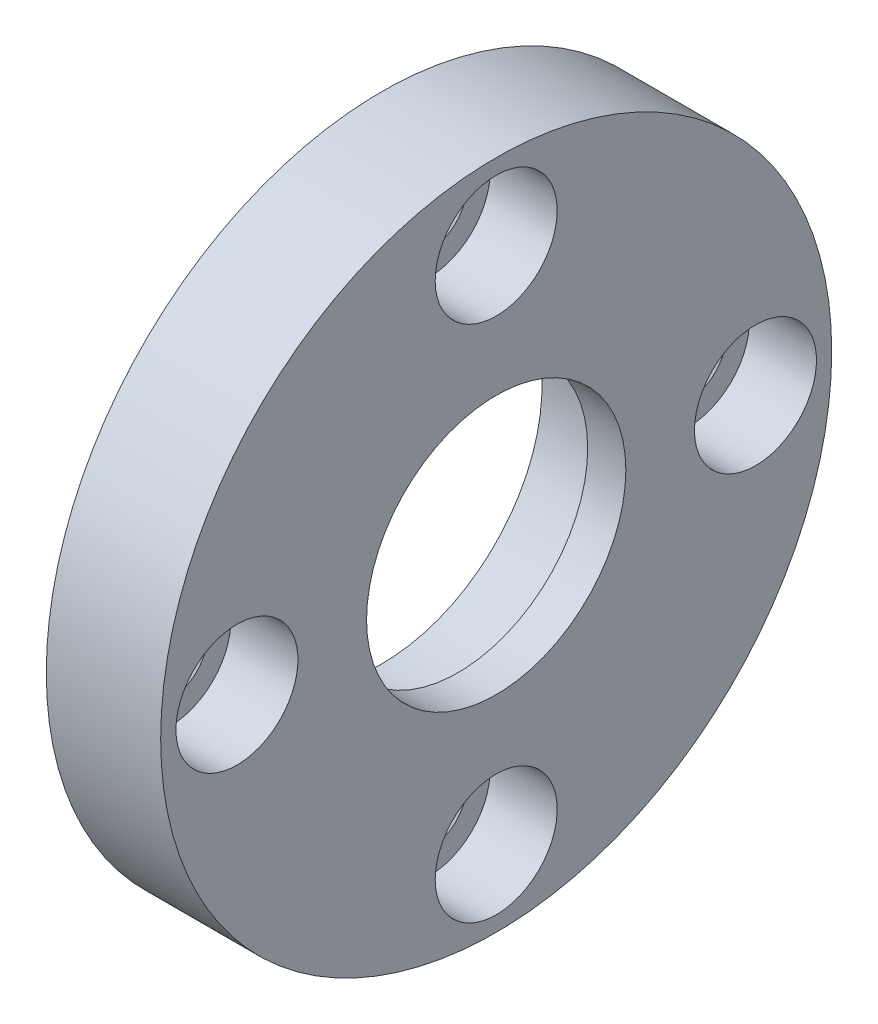
SolidWorks part; units mm, degrees
ref_plane "正面" through (0, 0, 0) normal (0, 0, 1) x (1, 0, 0)
ref_plane "平面" through (0, 0, 0) normal (0, 1, 0) x (1, 0, 0)
ref_plane "右側面" through (0, 0, 0) normal (1, 0, 0) x (0, 0, -1)
ref_plane "平面1" through (0, 0, 0) normal (0, 0, 1) x (1, 0, 0)
sketch "ｽｹｯﾁ1" plane through (0, 0, 0) normal (0, 0, 1) x (1, 0, 0)
  line L0 (-3.75, 0) -> (-3.75, 22)
  line L1 (-3.75, 22) -> (3.75, 22)
  line L2 (3.75, 22) -> (3.75, 0)
  line L3 (3.75, 0) -> (-3.75, 0)
  line L4 (3.75, 0) -> (-3.75, 0) construction
revolve "回転1" add sketch "ｽｹｯﾁ1" angle 360 about L4
ref_plane "平面2" through (0, 0, 0) normal (0, 0, 1) x (1, 0, 0)
sketch "ｽｹｯﾁ2" plane through (0, 0, 0) normal (0, 0, 1) x (1, 0, 0)
  line L0 (-3.75, 0) -> (-3.75, 10.5)
  line L1 (-3.75, 10.5) -> (1.25, 10.5)
  line L2 (1.25, 10.5) -> (1.25, 8.5)
  line L3 (1.25, 8.5) -> (3.75, 8.5)
  line L4 (3.75, 8.5) -> (3.75, 0)
  line L5 (3.75, 0) -> (-3.75, 0)
  line L6 (3.75, 0) -> (-3.75, 0) construction
revolve "ｶｯﾄ - 回転1" cut sketch "ｽｹｯﾁ2" angle 360 about L6
ref_plane "平面3" through (0, 0, 0) normal (0, 0, 1) x (1, 0, 0)
sketch "ｽｹｯﾁ3" plane through (0, 0, 0) normal (0, 0, 1) x (1, 0, 0)
  line L0 (-3.75, 17) -> (-3.75, 19.5)
  line L1 (-3.75, 19.5) -> (-3.317, 19.067)
  line L2 (-3.317, 19.067) -> (-1.083, 19.067)
  line L3 (-1.083, 19.067) -> (-0.65, 19.5)
  line L4 (-0.65, 19.5) -> (-0.65, 21)
  line L5 (-0.65, 21) -> (3.75, 21)
  line L6 (3.75, 21) -> (3.75, 17)
  line L7 (3.75, 17) -> (-3.75, 17)
  line L8 (3.75, 17) -> (-3.75, 17) construction
revolve "ｶｯﾄ - 回転2" cut sketch "ｽｹｯﾁ3" angle 360 about L8
ref_plane "平面4" through (0, 0, 17) normal (0, 0, 1) x (1, 0, 0)
sketch "ｽｹｯﾁ4" plane through (0, 0, 17) normal (0, 0, 1) x (1, 0, 0)
  line L0 (-3.75, 0) -> (-3.75, 2.5)
  line L1 (-3.75, 2.5) -> (-3.317, 2.067)
  line L2 (-3.317, 2.067) -> (-1.083, 2.067)
  line L3 (-1.083, 2.067) -> (-0.65, 2.5)
  line L4 (-0.65, 2.5) -> (-0.65, 4)
  line L5 (-0.65, 4) -> (3.75, 4)
  line L6 (3.75, 4) -> (3.75, 0)
  line L7 (3.75, 0) -> (-3.75, 0)
  line L8 (3.75, 0) -> (-3.75, 0) construction
revolve "ｶｯﾄ - 回転3" cut sketch "ｽｹｯﾁ4" angle 360 about L8
ref_plane "平面5" through (0, 0, 0) normal (0, 0, 1) x (1, 0, 0)
sketch "ｽｹｯﾁ5" plane through (0, 0, 0) normal (0, 0, 1) x (1, 0, 0)
  line L0 (-3.75, -17) -> (-3.75, -14.5)
  line L1 (-3.75, -14.5) -> (-3.317, -14.933)
  line L2 (-3.317, -14.933) -> (-1.083, -14.933)
  line L3 (-1.083, -14.933) -> (-0.65, -14.5)
  line L4 (-0.65, -14.5) -> (-0.65, -13)
  line L5 (-0.65, -13) -> (3.75, -13)
  line L6 (3.75, -13) -> (3.75, -17)
  line L7 (3.75, -17) -> (-3.75, -17)
  line L8 (3.75, -17) -> (-3.75, -17) construction
revolve "ｶｯﾄ - 回転4" cut sketch "ｽｹｯﾁ5" angle 360 about L8
ref_plane "平面6" through (0, 0, -17) normal (0, 0, 1) x (1, 0, 0)
sketch "ｽｹｯﾁ6" plane through (0, 0, -17) normal (0, 0, 1) x (1, 0, 0)
  line L0 (-3.75, 0) -> (-3.75, 2.5)
  line L1 (-3.75, 2.5) -> (-3.317, 2.067)
  line L2 (-3.317, 2.067) -> (-1.083, 2.067)
  line L3 (-1.083, 2.067) -> (-0.65, 2.5)
  line L4 (-0.65, 2.5) -> (-0.65, 4)
  line L5 (-0.65, 4) -> (3.75, 4)
  line L6 (3.75, 4) -> (3.75, 0)
  line L7 (3.75, 0) -> (-3.75, 0)
  line L8 (3.75, 0) -> (-3.75, 0) construction
revolve "ｶｯﾄ - 回転5" cut sketch "ｽｹｯﾁ6" angle 360 about L8
